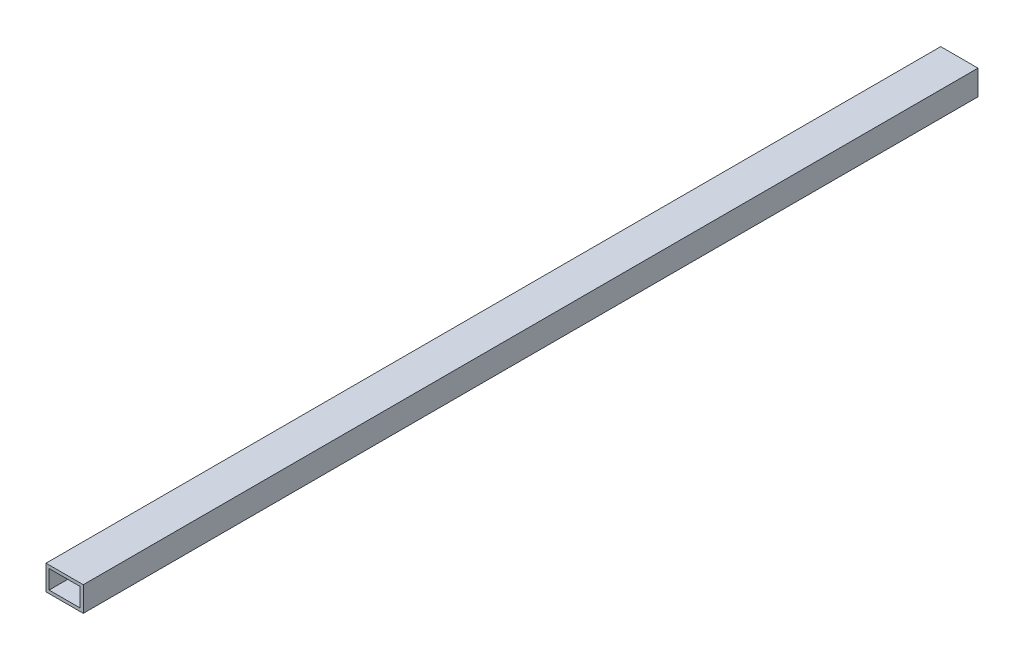
SolidWorks part; units mm, degrees
ref_plane "Front Plane" through (0, 0, 0) normal (0, 0, 1) x (1, 0, 0)
ref_plane "Top Plane" through (0, 0, 0) normal (0, 1, 0) x (1, 0, 0)
ref_plane "Right Plane" through (0, 0, 0) normal (1, 0, 0) x (0, 0, -1)
sketch "Sketch1" plane through (0, 0, 0) normal (0, 0, 1) x (1, 0, 0)
  line L0 (-15.875, 9.525) -> (15.875, 9.525)
  line L2 (-19.05, 12.7) -> (19.05, 12.7)
  line L3 (-19.05, 12.7) -> (-19.05, -12.7)
  line L4 (-19.05, -12.7) -> (19.05, -12.7)
  line L5 (19.05, 12.7) -> (19.05, -12.7)
  line L10 (15.875, 9.525) -> (15.875, -9.525)
  line L11 (-15.875, -9.525) -> (15.875, -9.525)
  line L12 (-15.875, 9.525) -> (-15.875, -9.525)
  point P12 (0, 12.7)
  point P14 (19.05, 0)
  dimension "Wall Thickness" = 3.175
  dimension "Outside Width" = 38.1
  dimension "Outside Height" = 25.4
  dimension "Inside Height" = 19.05
  dimension "Inside Width" = 31.75
sketch "Sketch2" plane through (0, 0, 0) normal (1, 0, 0) x (0, 0, -1)
  line L0 (457.2, 0) -> (-457.2, 0)
  point P4 (0, 0)
  point P7 (-457.2, 0)
  point P10 (457.2, 0)
  dimension "Length" = 914.4
sketch "Sketch3" plane through (0, 0, 0) normal (0, 0, 1) x (1, 0, 0)
  line L21 (19.05, 12.7) -> (-19.05, 12.7)
  line L22 (19.05, -12.7) -> (19.05, 12.7)
  line L23 (-19.05, -12.7) -> (19.05, -12.7)
  line L24 (-19.05, 12.7) -> (-19.05, -12.7)
  line L25 (19.05, 12.7) -> (-19.05, 12.7)
  line L26 (19.05, -12.7) -> (19.05, 12.7)
  line L27 (-19.05, -12.7) -> (19.05, -12.7)
  line L28 (-19.05, 12.7) -> (-19.05, -12.7)
  line L29 (15.875, 9.525) -> (-15.875, 9.525)
  line L30 (15.875, -9.525) -> (15.875, 9.525)
  line L31 (-15.875, -9.525) -> (15.875, -9.525)
  line L32 (-15.875, 9.525) -> (-15.875, -9.525)
  line L33 (15.875, 9.525) -> (-15.875, 9.525)
  line L34 (15.875, -9.525) -> (15.875, 9.525)
  line L35 (-15.875, -9.525) -> (15.875, -9.525)
  line L36 (-15.875, 9.525) -> (-15.875, -9.525)
  dimension "D1" = 0
  dimension "D2" = 0
extrude "Boss-Extrude1" add sketch "Sketch3" along normal up to vertex (457.2 mm away) and the other way up to vertex (457.2 mm away) up to point (0, 0, 457.2) other way up to point (0, 0, -457.2)
sketch "Drawing Reference" plane through (0, 0, 0) normal (1, 0, 0) x (0, 0, -1)
  line L0 (-457.2, 0) -> (457.2, 0) construction
  line L1 (0, -12.7) -> (0, 12.7) construction
  line L2 (-457.2, -12.7) -> (457.2, -12.7) construction
  line L5 (-457.2, 12.7) -> (457.2, 12.7) construction
  point P7 (-429.768, 0)
  point P8 (429.768, 0)
  dimension "D1" = 27.432
equation "\"D1@Drawing Reference\"=\"Outside Width@Sketch1\" * 0.72"
